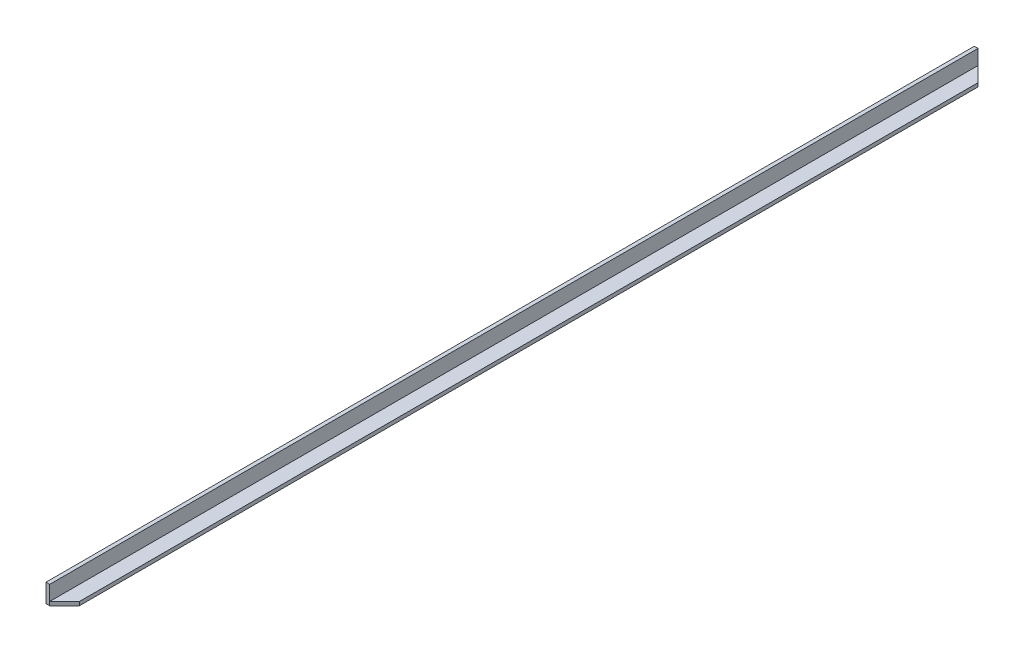
SolidWorks part; units mm, degrees
ref_plane "Front" through (0, 0, 0) normal (0, 0, 1) x (1, 0, 0)
ref_plane "Top" through (0, 0, 0) normal (0, 1, 0) x (1, 0, 0)
ref_plane "Right" through (0, 0, 0) normal (1, 0, 0) x (0, 0, -1)
sketch "Эскиз1" plane through (0, 0, 0) normal (0, 0, 1) x (1, 0, 0)
  line L0 (-10, 0) -> (10, 0)
  line L1 (-10, 0) -> (-10, 20)
  line L2 (-10, 20) -> (-6, 20)
  line L3 (-6, 20) -> (-6, 4)
  line L4 (-6, 4) -> (10, 4)
  line L5 (10, 4) -> (10, 0)
  dimension "D1" = 20
  dimension "D2" = 4
extrude "Бобышка-Вытянуть1" add sketch "Эскиз1" along normal blind 1000
sketch "Эскиз2" plane through (0, 4, 0) normal (0, 1, 0) x (1, 0, 0)
  line L0 (-6, 0) -> (10, -16)
  line L1 (10, -1000) -> (10, 0) construction
  line L2 (10, -16) -> (10, 0)
  line L3 (10, 0) -> (-6, 0)
extrude "Вырез-Вытянуть1" cut sketch "Эскиз2" against normal through all
sketch "Эскиз3" plane through (0, 4, 0) normal (0, 1, 0) x (1, 0, 0)
  line L0 (-6, -1000) -> (10, -984)
  line L1 (10, -1000) -> (10, -16) construction
  line L2 (10, -984) -> (10, -1000)
  line L3 (10, -1000) -> (-6, -1000)
extrude "Вырез-Вытянуть2" cut sketch "Эскиз3" against normal through all
